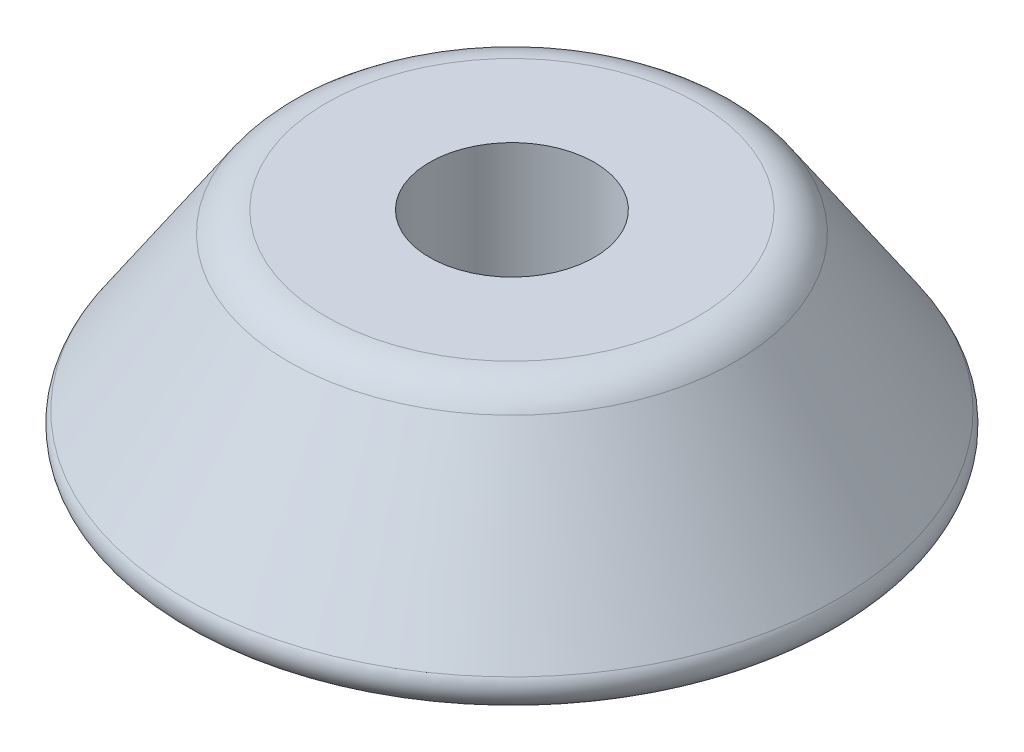
SolidWorks part; units mm, degrees
ref_plane "Front Plane" through (0, 0, 0) normal (0, 0, 1) x (1, 0, 0)
ref_plane "Top Plane" through (0, 0, 0) normal (0, 1, 0) x (1, 0, 0)
ref_plane "Right Plane" through (0, 0, 0) normal (1, 0, 0) x (0, 0, -1)
sketch "Sketch1" plane through (0, 0, 0) normal (0, 0, 1) x (1, 0, 0)
  line L0 (0, 0) -> (0, 16.4042) construction
  line L1 (4, 0) -> (4, 10)
  line L2 (4, 10) -> (9, 10)
  line L4 (15, 0) -> (4, 0)
  line L5 (15.8309, 1.5564) -> (10.8308, 9.0227)
  arc A0 (9, 10) -> (10.8308, 9.0227) centre (9, 7.7966) cw
  arc A1 (15, 0) -> (15.8309, 1.5564) centre (15, 1) ccw
  dimension "D5" = 1
  dimension "D1" = 8
  dimension "D2" = 10
  dimension "D3" = 30
  dimension "D4" = 5
revolve "Revolve1" add sketch "Sketch1" angle 360 about L0
